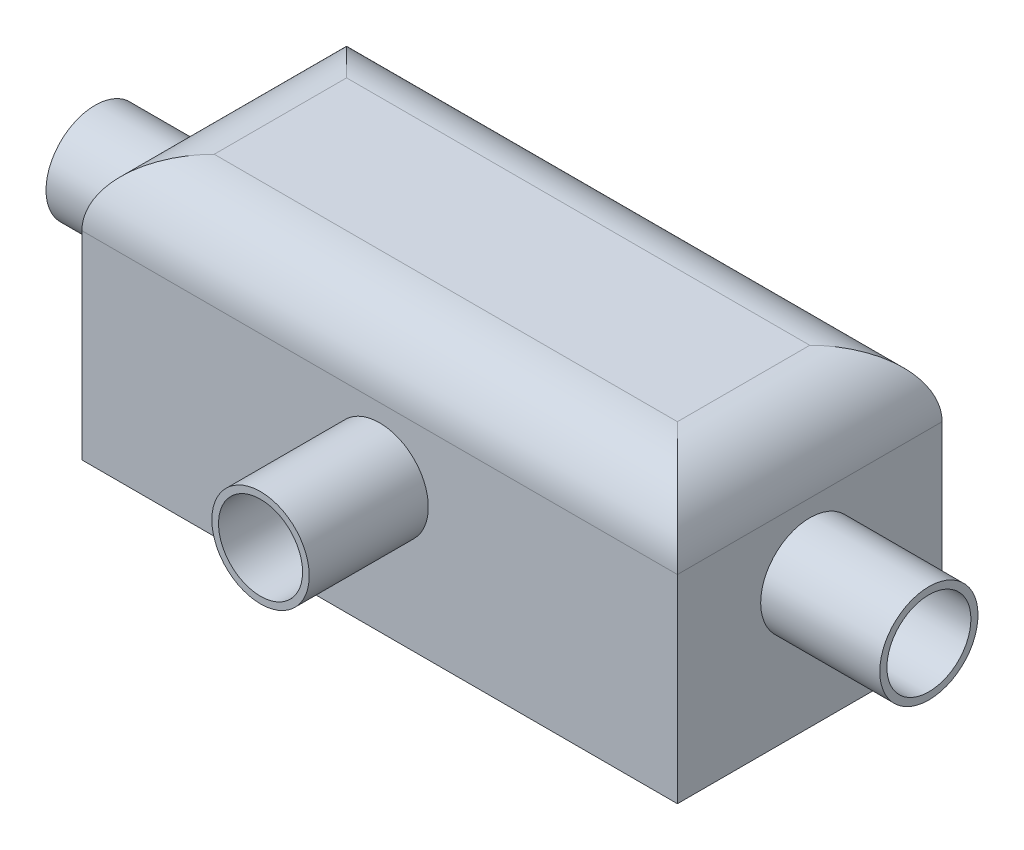
SolidWorks part; units mm, degrees
ref_plane "Alzado" through (0, 0, 0) normal (0, 0, 1) x (1, 0, 0)
ref_plane "Planta" through (0, 0, 0) normal (0, 1, 0) x (1, 0, 0)
ref_plane "Vista lateral" through (0, 0, 0) normal (1, 0, 0) x (0, 0, -1)
sketch "Croquis1" plane through (0, 0, 0) normal (0, 1, 0) x (1, 0, 0)
  line L1 (-45, 20) -> (45, 20)
  line L2 (-45, 20) -> (-45, -20)
  line L3 (-45, -20) -> (45, -20)
  line L4 (45, 20) -> (45, -20)
  line L5 (-45, 20) -> (45, -20) construction
  line L6 (-45, -20) -> (45, 20) construction
  point P0 (0, 0)
  dimension "D1" = 90
  dimension "D2" = 40
extrude "Saliente-Extruir1" add sketch "Croquis1" along normal blind 40
sketch "Croquis2" plane through (45, 0, 0) normal (1, 0, 0) x (0, 0, -1)
  line L0 (0, 40) -> (0, 0) construction
  line L1 (-20, 40) -> (20, 40) construction
  line L2 (0, 0) -> (0, 20) construction
  line L3 (0, 20) -> (20, 20) construction
  line L4 (20, 40) -> (20, 0) construction
  circle A0 centre (0, 20) radius 6.35
  circle A1 centre (0, 20) radius 7.4214
  dimension "D1" = 12.7
extrude "Saliente-Extruir2" add sketch "Croquis2" along normal blind 18
sketch "Croquis3" plane through (-45, 0, 0) normal (-1, 0, 0) x (0, 0, 1)
  circle A0 centre (0, 20) radius 6.35
  circle A1 centre (0, 20) radius 7.4214
extrude "Saliente-Extruir3" add sketch "Croquis3" along normal blind 18
sketch "Croquis4" plane through (0, 0, 20) normal (0, 0, 1) x (1, 0, 0)
  line L0 (0, 0) -> (0, 40) construction
  line L1 (-45, 40) -> (45, 40) construction
  line L2 (0, 40) -> (0, 20) construction
  line L3 (0, 20) -> (45, 20) construction
  line L4 (45, 12.5786) -> (45, 27.4214) construction
  circle A0 centre (0, 20) radius 7.3563
  circle A1 centre (0, 20) radius 6.35
  dimension "D1" = 12.7
extrude "Saliente-Extruir4" add sketch "Croquis4" along normal blind 18
fillet "Redondeo1" radius 10 4 edges at (-45, 40, 0) (45, 40, 0) (0, 40, -20) (0, 40, 20)
